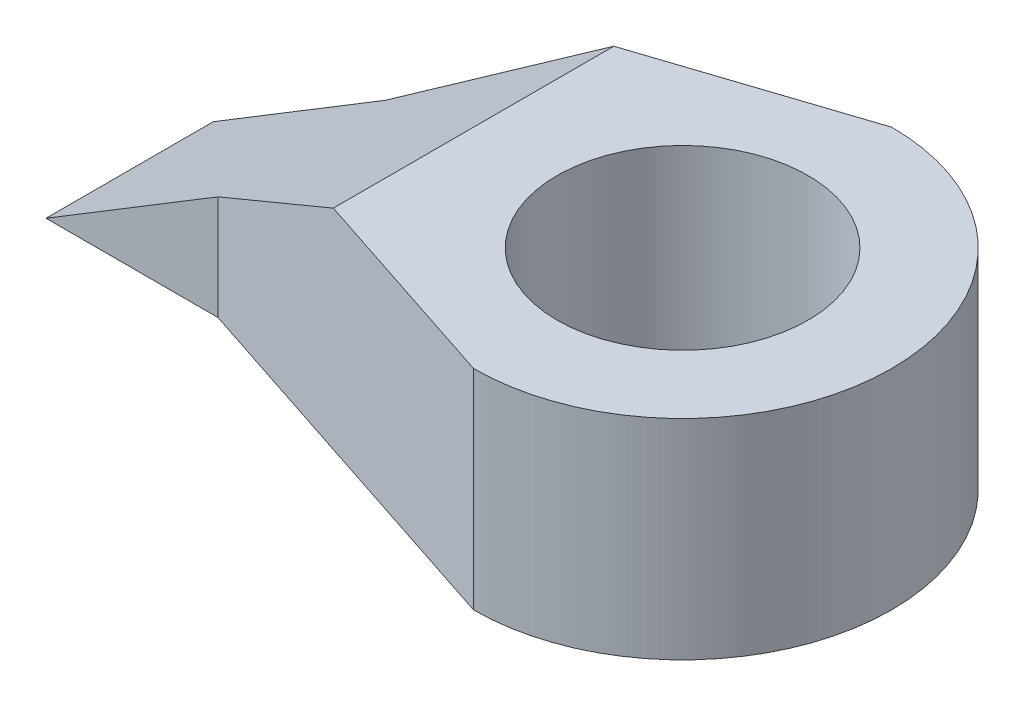
SolidWorks part; units mm, degrees
ref_plane "Front Plane" through (0, 0, 0) normal (0, 0, 1) x (1, 0, 0)
ref_plane "Top Plane" through (0, 0, 0) normal (0, 1, 0) x (1, 0, 0)
ref_plane "Right Plane" through (0, 0, 0) normal (1, 0, 0) x (0, 0, -1)
sketch "Sketch1" plane through (0, 0, 0) normal (0, 0, 1) x (1, 0, 0)
  line L0 (0, 0) -> (8.2266, 5)
  line L1 (8.2266, 5) -> (8.2266, 0)
  line L2 (8.2266, 0) -> (0, 0)
  dimension "D1" = 5
  dimension "D2" = 9.6269
extrude "Boss-Extrude4" add sketch "Sketch1" along normal blind 4
sketch "Sketch7" plane through (0, 0, 0) normal (0, 1, 0) x (1, 0, 0)
  line L0 (8.2266, -2) -> (18.2266, -2) construction
  line L1 (8.2266, -4) -> (8.2266, 0) construction
  line L2 (13.2266, 3) -> (4.1133, 0)
  line L3 (8.2266, 0) -> (0, 0) construction
  line L4 (13.2266, -7) -> (4.1133, -4)
  line L5 (8.2266, -4) -> (0, -4) construction
  line L7 (4.1133, 0) -> (8.2266, 0)
  line L8 (8.2266, 0) -> (8.2266, -4)
  line L9 (8.2266, -4) -> (4.1133, -4)
  arc A0 (13.2266, -7) -> (13.2266, 3) centre (13.2266, -2) ccw
  dimension "D1" = 10
  dimension "D2" = 5
extrude "Boss-Extrude6" add sketch "Sketch7" along normal blind 5
sketch "Sketch8" plane through (0, 0, 0) normal (0, 0, 1) x (1, 0, 0)
  line L0 (4.1133, 2.5) -> (4.1133, 5)
  line L1 (4.1133, 5) -> (8.2266, 5)
  line L2 (8.2266, 5) -> (4.1133, 2.5)
extrude "Cut-Extrude1" cut sketch "Sketch8" against normal up to next
ref_plane "Plane1" through (0, 0, 2) normal (0, 0, 1) x (1, 0, 0)
mirror "Mirror1" about plane through (0, 0, 2) normal (0, 0, 1) of "Cut-Extrude1"
sketch "Sketch9" plane through (0, 5, 0) normal (0, 1, 0) x (1, 0, 0)
  line L0 (-2.75, -2) -> (2.75, -2) construction
  circle A0 centre (13.2266, -2) radius 3
  arc A1 (13.2266, -7) -> (13.2266, 3) centre (13.2266, -2) ccw construction
  dimension "D1" = 6
extrude "Cut-Extrude2" cut sketch "Sketch9" against normal up to next
